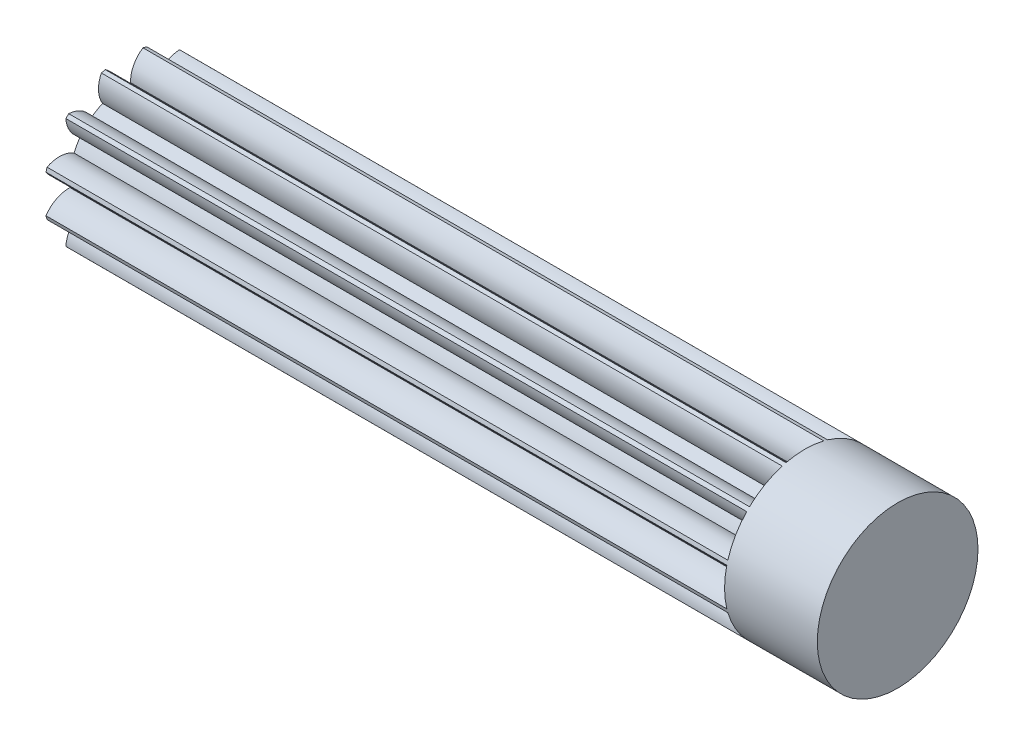
SolidWorks part; units mm, degrees
ref_plane "Plane1" through (0, 0, 0) normal (0, 0, 1) x (1, 0, 0)
ref_plane "Plane2" through (0, 0, 0) normal (0, 1, 0) x (1, 0, 0)
ref_plane "Plane3" through (0, 0, 0) normal (1, 0, 0) x (0, 0, -1)
sketch "HoldingSke" plane through (0, 0, 0) normal (0, 1, 0) x (1, 0, 0)
  line L0 (0, 0) -> (0.9781, -0.2079)
  line L1 (-15, 0) -> (100, 0) construction
  line L2 (0, 0) -> (-2.1039, 2.3779)
  line L3 (0, 0) -> (-11.863, 4.5341)
  line L4 (0, 0) -> (8.4473, 1.7955)
  line L5 (0, 0) -> (-46.8476, -17.4728)
  line L6 (0, 0) -> (-9.9476, -6.7116)
  line L7 (-2.1039, 2.3779) -> (8.6586, 51.2059)
  line L8 (-76.2, 54.61) -> (-76.1, 54.61)
  line L9 (-71.009, 38.7566) -> (-53.1078, 45.2721)
  line L10 (-76.2, 71.12) -> (104.1128, 71.12)
  line L11 (0, 0) -> (-12, 0)
  line L12 (-76.2, 101.6) -> (-76.162, 101.6)
  line L13 (24.9733, 27.94) -> (52.9518, 28.4284)
  line L14 (24.9733, 27.94) -> (24.9743, 27.94)
  line L15 (24.9733, 27.94) -> (100.4006, 29.5858)
  line L16 (-63.627, -1) -> (-12.827, -1)
  circle A0 centre (0, 0) radius 0.4
  circle A1 centre (0, 0) radius 4.749
  circle A2 centre (0, 0) radius 37.5
  circle A3 centre (0, 0) radius 0.4
  dimension "MHD" = 9.498
  dimension "Hub_dia" = 75
  dimension "Bore" = 0.8
  dimension "MBD" = 0.8
  dimension "Num_teeth" = 12
  dimension "Pitch" = 1
  dimension "Overall_len" = 50
  dimension "Show_teeth" = 12
  dimension "Thickness" = 12
  dimension "OAL" = 50.0001
  dimension "T_dim" = 0.1
  dimension "Ap" = 20
  dimension "H" = 19.05
  dimension "Pitch_radius" = 180.3128
  dimension "Width" = 12
  dimension "Backlash" = 0.038
  dimension "Addendum_fac" = 1
  dimension "Dedendum_fac" = 1.25
  dimension "Clearance_fac" = 0.25
  dimension "Dedendum_add" = 0.001
  dimension "Module" = 1
sketch "BasProSke" plane through (0, 0, 0) normal (0, 1, 0) x (1, 0, 0)
  line L0 (-10, 0) -> (60, 0) construction
  line L1 (0, 0) -> (0, 7)
  line L2 (0, 0) -> (59.315, 0)
  line L3 (59.315, 0) -> (59.315, 7)
  line L4 (59.315, 7) -> (0, 7)
  dimension "Thickness" = 59.315
  dimension "Diameter" = 14
revolve "Base-Revolve" add sketch "BasProSke" angle 360 about L0
sketch "TooCutSke" plane through (0, 0, 0) normal (1, 0, 0) x (0, 0, -1)
  line L1 (0, 0) -> (0, 107) construction
  line L2 (0, 0) -> (-0.8496, 5.9395) construction
  line L3 (0, 0) -> (-3.0836, 11.5081) construction
  line L4 (-0.8496, 5.9395) -> (-1.5418, 5.7541) construction
  arc A0 (0.5622, 4.7156) -> (-0.5622, 4.7156) centre (0, 0) ccw
  arc A1 (1.6729, 6.8233) -> (-1.6729, 6.8233) centre (0, 0) ccw
  circle A2 centre (0, 0) radius 6 construction
  circle A3 centre (0, 0) radius 5.6382 construction
  arc A4 (-0.5622, 4.7156) -> (-1.6729, 6.8233) centre (-2.9608, 4.7982) ccw
  arc A5 (1.6729, 6.8233) -> (0.5622, 4.7156) centre (2.9608, 4.7982) ccw
  dimension "Root_dia" = 9.498
  dimension "Overcut_dia" = 14.0508
  dimension "Pitch_dia" = 12
  dimension "Base_dia" = 11.2763
  dimension "Flank_rad" = 2.4
  dimension "Half_ang" = 15
  dimension "Half_CT" = 0.7167
extrude "ToothCut" cut sketch "TooCutSke" along normal through all
fillet "Breaks" [suppressed] radius 0.02
fillet "RootFillets" [suppressed] radius 0.251
pattern_circular "TeethCuts" count 12 every 30 about axis through (-10, 0, 0) along (1, 0, 0) of "ToothCut", "RootFillets", "Breaks"
sketch "HubNeaOneSke" plane through (0, 0, 0) normal (-1, 0, 0) x (0, 0, 1)
  circle A0 centre (0, 0) radius 4.749
  dimension "Diameter" = 9.498
extrude "HubNearOne" [suppressed] add sketch "HubNeaOneSke" along normal blind 10.4351
sketch "HubNeaBotSke" plane through (0, 0, 0) normal (-1, 0, 0) x (0, 0, 1)
  circle A0 centre (0, 0) radius 4.749
  dimension "Diameter" = 9.498
extrude "HubNearBoth" [suppressed] add sketch "HubNeaBotSke" along normal blind 5.2175
ref_plane "FarPln" through (59.315, 0, 0) normal (1, 0, 0) x (0, 0, -1)
sketch "HubFarSke" plane through (59.315, 0, 0) normal (1, 0, 0) x (0, 0, -1)
  circle A0 centre (0, 0) radius 4.749
  dimension "Diameter" = 9.498
extrude "HubFar" [suppressed] add sketch "HubFarSke" along normal blind 5.2175
sketch "BorSke" plane through (0, 0, 0) normal (1, 0, 0) x (0, 0, -1)
  circle A0 centre (0, 0) radius 0.4
  dimension "Diameter" = 0.8
extrude "Bore" cut sketch "BorSke" along normal mid plane 100.0001
sketch "KeySke" plane through (0, 0, 0) normal (1, 0, 0) x (0, 0, -1)
  line L0 (-0.05, 0) -> (-0.05, 0.5)
  line L1 (-0.05, 0.5) -> (0.05, 0.5)
  line L2 (0.05, 0.5) -> (0.05, 0)
  line L3 (0, 0) -> (0, 34) construction
  line L4 (-0.05, 0) -> (0.05, 0)
  dimension "Offset" = 0.5
  dimension "Width" = 0.1
extrude "Keyway" [suppressed] cut sketch "KeySke" along normal mid plane 100.0001
pattern_circular "Keyway2" [suppressed] count 2 every 90 about axis through (-10, 0, 0) along (1, 0, 0)
sketch "Sketch1" plane through (0, 0, 0) normal (-1, 0, 0) x (0, 0, 1)
  circle A0 centre (0, 0) radius 7
scale "Scale1" scale about centroid uniform scaling yes scale factor 2
sketch "Sketch6" plane through (88.9537, 0, 0) normal (1, 0, 0) x (0, 0, -1)
  circle A0 centre (0, 0) radius 11.811 construction
  dimension "D1" = 23.622
sketch "Sketch9" plane through (88.9537, 0, 0) normal (1, 0, 0) x (0, 0, -1)
  circle A0 centre (0, 0) radius 14
extrude "Boss-Extrude1" add sketch "Sketch9" along normal blind 16.163
scale "Scale2" scale about centroid uniform scaling yes scale factor 0.666667
sketch "Sketch10" plane through (-6.1572, 0, 0) normal (-1, 0, 0) x (0, 0, 1)
  circle A0 centre (0, 0) radius 5
  dimension "D1" = 10
extrude "Cut-Extrude1" cut sketch "Sketch10" against normal blind 4
sketch "Sketch11" plane through (-2.1572, 0, 0) normal (-1, 0, 0) x (0, 0, 1)
  line L3 (4.5, 0) -> (4.5, 2.1794)
  line L4 (4.5, 0) -> (4.5, -2.1794)
  arc A2 (4.5, 2.1794) -> (4.5, -2.1794) centre (0, 0) ccw
extrude "Cut-Extrude3" cut sketch "Sketch11" against normal blind 20.25
equation "' \"Module@HoldingSke\" = 6.35"
equation "' \"Num_teeth@HoldingSke\" = 12"
equation "' \"Ap@HoldingSke\" =  20"
equation "' \"Ap@HoldingSke\" = 20"
equation "' \"Width@HoldingSke\" = 0.5 * 25.4"
equation "' \"Hub_dia@HoldingSke\"= 1 * 25.4"
equation "' \"Hub_dia@HoldingSke\" = 1 * 25.4"
equation "' \"Overall_len@HoldingSke\" = 1.0 * 25.4"
equation "' \"Bore@HoldingSke\" = 0.75 * 25.4"
equation "' \"T_dim@HoldingSke\" = 0.1 * 25.4"
equation "' \"Width@KeySke\" = 0.25 * 25.4"
equation "' \"Show_teeth@HoldingSke\" = 13"
equation "' \"Backlash@HoldingSke\" = 0.009 * 25.4"
equation "' \"Addendum_fac@HoldingSke\" = 1.0"
equation "' \"Dedendum_fac@HoldingSke\" = 1.25"
equation "' \"Dedendum_add@HoldingSke\" = 0.00005 * 25.4"
equation "' \"Clearance_fac@HoldingSke\" = 0.25"
equation "\"Pitch@HoldingSke\" = 1 / \"Module@HoldingSke\""
equation "\"Overcut_dia@TooCutSke\" = (\"Num_teeth@HoldingSke\" + 2 * \"Addendum_fac@HoldingSke\") / \"Pitch@HoldingSke\" + 0.002 * 25.4"
equation "\"Pitch_dia@TooCutSke\" = \"Num_teeth@HoldingSke\" / \"Pitch@HoldingSke\""
equation "\"Base_dia@TooCutSke\" = \"Num_teeth@HoldingSke\" / \"Pitch@HoldingSke\" * cos((\"Ap@HoldingSke\"  * 3.14159265 / 180))"
equation "\"Root_dia@TooCutSke\" = (\"Num_teeth@HoldingSke\" + 2) / \"Pitch@HoldingSke\" - 2 * (\"Addendum_fac@HoldingSke\" + \"Dedendum_fac@HoldingSke\") / \"Pitch@HoldingSke\" - \"Dedendum_add@HoldingSke\" * 2"
equation "\"Half_ang@TooCutSke\" = 180 / \"Num_teeth@HoldingSke\""
equation "\"Half_CT@TooCutSke\" = \"Num_teeth@HoldingSke\" / \"Pitch@HoldingSke\" * sin((3.14159265 / 2 / \"Num_teeth@HoldingSke\")) / 2 - 7 * \"Backlash@HoldingSke\" / 4"
equation "\"Flank_rad@TooCutSke\" = \"Num_teeth@HoldingSke\" / \"Pitch@HoldingSke\" / 5"
equation "\"Radius@RootFillets\" = \"Clearance_fac@HoldingSke\" / \"Pitch@HoldingSke\" + \"Dedendum_add@HoldingSke\""
equation "\"Break_rad@Breaks\" = 0.02 / \"Pitch@HoldingSke\""
equation "\"Thickness@HoldingSke\" = \"Width@HoldingSke\""
equation "\"OAL@HoldingSke\" = \"Thickness@HoldingSke\""
equation "\"MHD@HoldingSke\" = (\"Num_teeth@HoldingSke\" + 2) / \"Pitch@HoldingSke\" - 2 * (\"Addendum_fac@HoldingSke\" + \"Dedendum_fac@HoldingSke\")  / \"Pitch@HoldingSke\" - \"Dedendum_add@HoldingSke\" * 2"
equation "\"MBD@HoldingSke\" = (\"Num_teeth@HoldingSke\" + 2) / \"Pitch@HoldingSke\" - 2 * (\"Addendum_fac@HoldingSke\" + \"Dedendum_fac@HoldingSke\")  / \"Pitch@HoldingSke\" - \"Dedendum_add@HoldingSke\" * 2 - 0.002 * 25.4"
equation "\"MHD@HoldingSke\" = ((sgn( \"MHD@HoldingSke\" - \"Hub_dia@HoldingSke\" )-1)*( \"MHD@HoldingSke\" - \"Hub_dia@HoldingSke\" ))/-2+ \"Hub_dia@HoldingSke\""
equation "\"MBD@HoldingSke\" = ((sgn( \"MBD@HoldingSke\" - \"Bore@HoldingSke\" )-1)*( \"MBD@HoldingSke\" - \"Bore@HoldingSke\" ))/-2+ \"Bore@HoldingSke\""
equation "\"OAL@HoldingSke\" = ((sgn( \"OAL@HoldingSke\" - \"Overall_len@HoldingSke\" )+1)*( \"OAL@HoldingSke\" - \"Overall_len@HoldingSke\" ))/2 + \"Overall_len@HoldingSke\" + 0.000002 * 25.4"
equation "\"Num_teeth@TeethCuts\" = int( \"Show_teeth@HoldingSke\" ) + 1"
equation "\"Num_teeth@TeethCuts\" = ((sgn( \"Num_teeth@TeethCuts\" - \"Num_teeth@HoldingSke\" )-1)*( \"Num_teeth@TeethCuts\" - \"Num_teeth@HoldingSke\" ))/-2+ \"Num_teeth@HoldingSke\""
equation "\"Num_teeth@TeethCuts\" = ((sgn( \"Num_teeth@TeethCuts\" - 2.0)+1)*( \"Num_teeth@TeethCuts\" - 2.0))/2 +2.0"
equation "\"Angle@TeethCuts\" = 360.0 / \"Num_teeth@HoldingSke\""
equation "\"Diameter@BasProSke\" = (\"Num_teeth@HoldingSke\" + 2 * \"Addendum_fac@HoldingSke\") / \"Pitch@HoldingSke\""
equation "' \"Fillet_rad@BasProSke\" =  \"Thickness@HoldingSke\" * 0.05"
equation "' \"Fillet_rad@BasProSke\" = \"Thickness@HoldingSke\" * 0.05"
equation "\"MHD@HoldingSke\" = ((sgn( \"MHD@HoldingSke\" - \"Root_dia@TooCutSke\" )-1)*( \"MHD@HoldingSke\" - \"Root_dia@TooCutSke\" ))/-2+ \"Root_dia@TooCutSke\""
equation "\"Diameter@HubNeaOneSke\" = \"MHD@HoldingSke\""
equation "\"Length@HubNearOne\" = \"OAL@HoldingSke\" - \"Thickness@BasProSke\""
equation "\"Diameter@HubNeaBotSke\" = \"MHD@HoldingSke\""
equation "\"Length@HubNearBoth\" = ( \"OAL@HoldingSke\" - \"Thickness@BasProSke\" ) / 2.0"
equation "\"Thickness@FarPln\" = \"Thickness@BasProSke\""
equation "\"Diameter@HubFarSke\" = \"MHD@HoldingSke\""
equation "\"Length@HubFar\" = ( \"OAL@HoldingSke\" - \"Thickness@BasProSke\" ) / 2.0"
equation "\"Diameter@BorSke\" = \"MBD@HoldingSke\""
equation "\"D1@Bore\" = \"OAL@HoldingSke\" * 2.0"
equation "\"D1@Keyway\" = \"OAL@HoldingSke\" * 2.0"
equation "\"Offset@KeySke\" = \"T_dim@HoldingSke\" + \"MBD@HoldingSke\" / 2.0"
